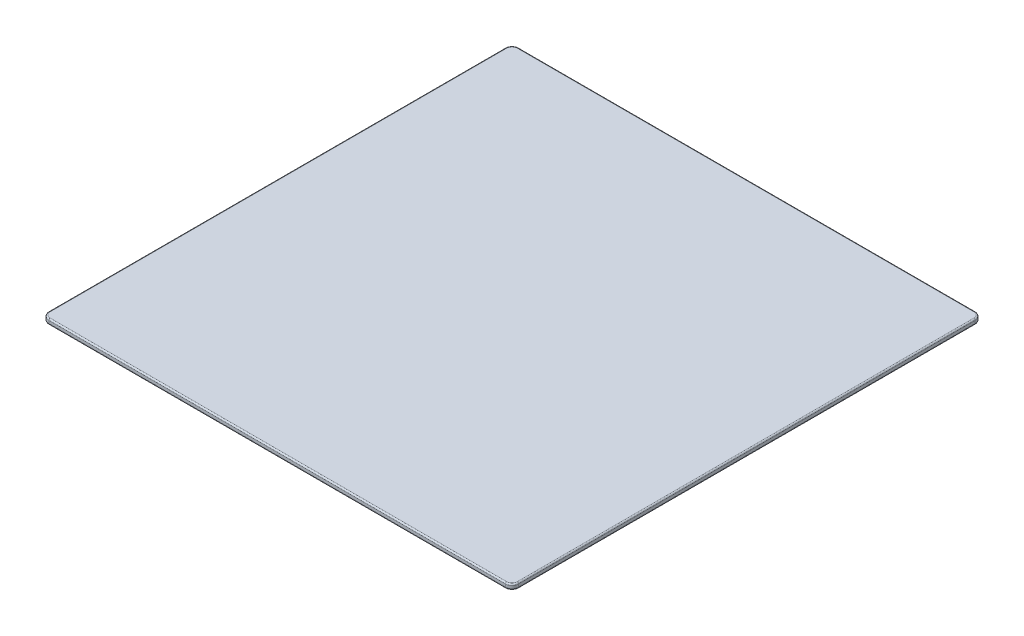
SolidWorks part; units mm, degrees
ref_plane "Front Plane" through (0, 0, 0) normal (0, 0, 1) x (1, 0, 0)
ref_plane "Top Plane" through (0, 0, 0) normal (0, 1, 0) x (1, 0, 0)
ref_plane "Right Plane" through (0, 0, 0) normal (1, 0, 0) x (0, 0, -1)
sketch "Sketch1" plane through (0, 0, 0) normal (0, 1, 0) x (1, 0, 0)
  line L1 (-170, 175) -> (170, 175)
  line L2 (-175, 170) -> (-175, -170)
  line L3 (-170, -175) -> (170, -175)
  line L4 (175, 170) -> (175, -170)
  line L5 (-175, 175) -> (175, -175) construction
  line L6 (-175, -175) -> (175, 175) construction
  arc A0 (170, -175) -> (175, -170) centre (170, -170) ccw
  arc A1 (-175, -170) -> (-170, -175) centre (-170, -170) ccw
  arc A2 (-170, 175) -> (-175, 170) centre (-170, 170) ccw
  arc A3 (170, 175) -> (175, 170) centre (170, 170) cw
  point P0 (0, 0)
  dimension "D2" = 5
  dimension "D1" = 350
extrude "Boss-Extrude1" add sketch "Sketch1" along normal blind 4
fillet "Fillet1" radius 1 16 edges at (175, 0, 0) (173.5355, 0, -173.5355) (0, 0, -175) (-173.5355, 0, -173.5355) (-175, 0, 0) (-173.5355, 0, 173.5355) (0, 0, 175) (173.5355, 0, 173.5355) (0, 4, 175) (-173.5355, 4, 173.5355) (-175, 4, 0) (-173.5355, 4, -173.5355) (0, 4, -175) (173.5355, 4, -173.5355) (175, 4, 0) (173.5355, 4, 173.5355)
